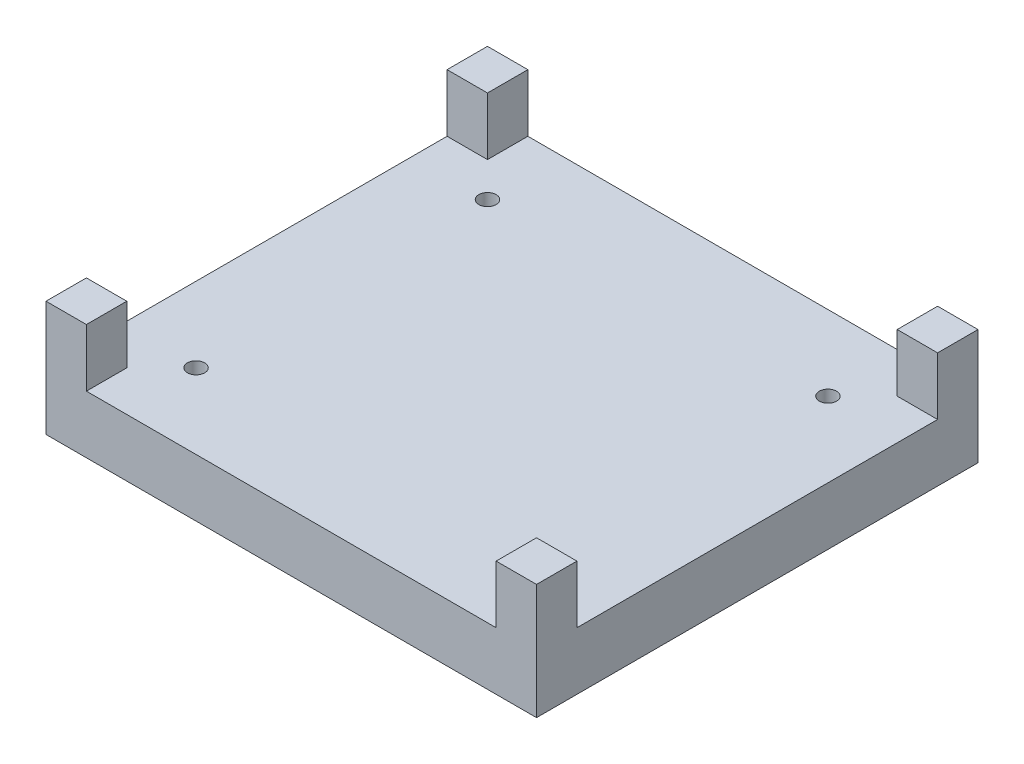
SolidWorks part; units mm, degrees
ref_plane "Front Plane" through (0, 0, 0) normal (0, 0, 1) x (1, 0, 0)
ref_plane "Top Plane" through (0, 0, 0) normal (0, 1, 0) x (1, 0, 0)
ref_plane "Right Plane" through (0, 0, 0) normal (1, 0, 0) x (0, 0, -1)
sketch "Sketch1" plane through (0, 0, 0) normal (0, 1, 0) x (1, 0, 0)
  line L0 (-42.5, -38.25) -> (-42.5, 38.25)
  line L1 (-42.5, -38.25) -> (42.5, -38.25)
  line L2 (-42.5, 38.25) -> (42.5, 38.25)
  line L3 (42.5, -38.25) -> (42.5, 38.25)
  line L4 (-42.5, -38.25) -> (42.5, 38.25) construction
  line L5 (-42.5, 38.25) -> (42.5, -38.25) construction
  line L6 (32.5, -28.25) -> (32.5, 28.25)
  line L7 (32.5, -28.25) -> (-32.5, -28.25)
  line L8 (32.5, 28.25) -> (-32.5, 28.25)
  line L9 (-32.5, -28.25) -> (-32.5, 28.25)
  line L10 (32.5, -28.25) -> (-32.5, 28.25) construction
  line L11 (32.5, 28.25) -> (-32.5, -28.25) construction
  circle A0 centre (-29.5, 25.25) radius 1.5
  circle A1 centre (-29.5, -25.25) radius 1.5
  circle A2 centre (29.5, -25.25) radius 1.5
  circle A3 centre (29.5, 25.25) radius 1.5
  circle A4 centre (-29.5, 25.25) radius 3
  circle A5 centre (29.5, -25.25) radius 3
  point P1 (0, 0)
  point P2 (0, 0)
  dimension "D5" = 3
  dimension "D6" = 6
  dimension "D7" = 6
  dimension "D1" = 10
  dimension "D2" = 10
  dimension "D3" = 65
  dimension "D4" = 56.5
extrude "Boss-Extrude1" add sketch "Sketch1" along normal blind 10 contours A5 L6 L8 A4 L9 L7 A3 A1 | L1 L3 L2 L0 L7 L9 L8 L6 | A4 A0 | A4 L8 L9 | A5 A2 | A5 L7 L6
sketch "Sketch2" plane through (0, 10, 0) normal (0, 1, 0) x (1, 0, 0)
  line L1 (-42.5, 38.25) -> (-35.5, 38.25)
  line L2 (-42.5, 38.25) -> (-42.5, 31.25)
  line L3 (-42.5, 31.25) -> (-35.5, 31.25)
  line L4 (-35.5, 38.25) -> (-35.5, 31.25)
  line L5 (42.5, 38.25) -> (35.5, 38.25)
  line L6 (42.5, 38.25) -> (42.5, 31.25)
  line L7 (42.5, 31.25) -> (35.5, 31.25)
  line L8 (35.5, 38.25) -> (35.5, 31.25)
  line L9 (-42.5, -38.25) -> (-35.5, -38.25)
  line L10 (-42.5, -38.25) -> (-42.5, -31.25)
  line L11 (-42.5, -31.25) -> (-35.5, -31.25)
  line L12 (-35.5, -38.25) -> (-35.5, -31.25)
  line L13 (42.5, -38.25) -> (35.5, -38.25)
  line L14 (42.5, -38.25) -> (42.5, -31.25)
  line L15 (42.5, -31.25) -> (35.5, -31.25)
  line L16 (35.5, -38.25) -> (35.5, -31.25)
  dimension "D1" = 7
  dimension "D2" = 7
  dimension "D3" = 7
  dimension "D4" = 7
  dimension "D5" = 7
  dimension "D6" = 7
  dimension "D7" = 7
  dimension "D8" = 7
extrude "Boss-Extrude2" add sketch "Sketch2" along normal blind 10
